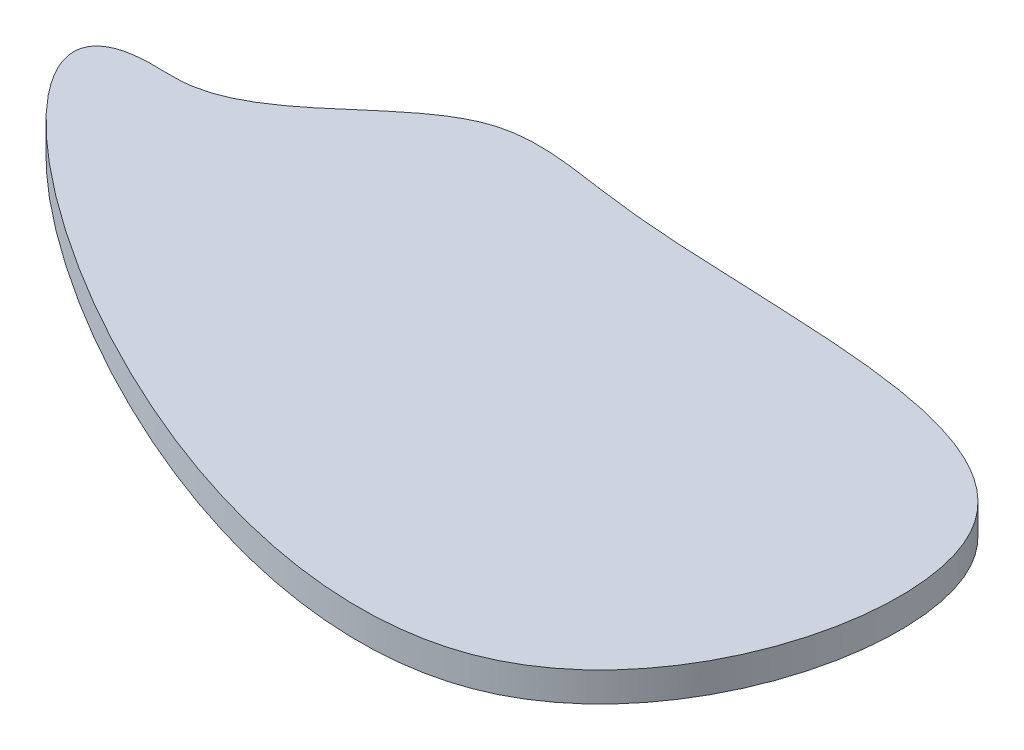
SolidWorks part; units mm, degrees
ref_plane "Front Plane" through (0, 0, 0) normal (0, 0, 1) x (1, 0, 0)
ref_plane "Top Plane" through (0, 0, 0) normal (0, 1, 0) x (1, 0, 0)
ref_plane "Right Plane" through (0, 0, 0) normal (1, 0, 0) x (0, 0, -1)
sketch "Sketch1" plane through (0, 0, 0) normal (0, 1, 0) x (1, 0, 0)
  spline S0 degree 3 poles (-96.8908, 5.8406) (23.9658, -1.9729) (52.4626, 49.68) (147.789, 28.0158) (306.2645, 51.6264) (229.9745, -233.7705) (-96.8908, 5.8406) (23.9658, -1.9729) (52.4626, 49.68) knots -0.582626 -0.393416 -0.013863 0 0.113908 0.176115 0.417374 0.606584 0.986137 1 1.113908 1.176115 1.417374 only from (0, 0) to (0, 0)
extrude "Boss-Extrude1" add sketch "Sketch1" along normal blind 10
